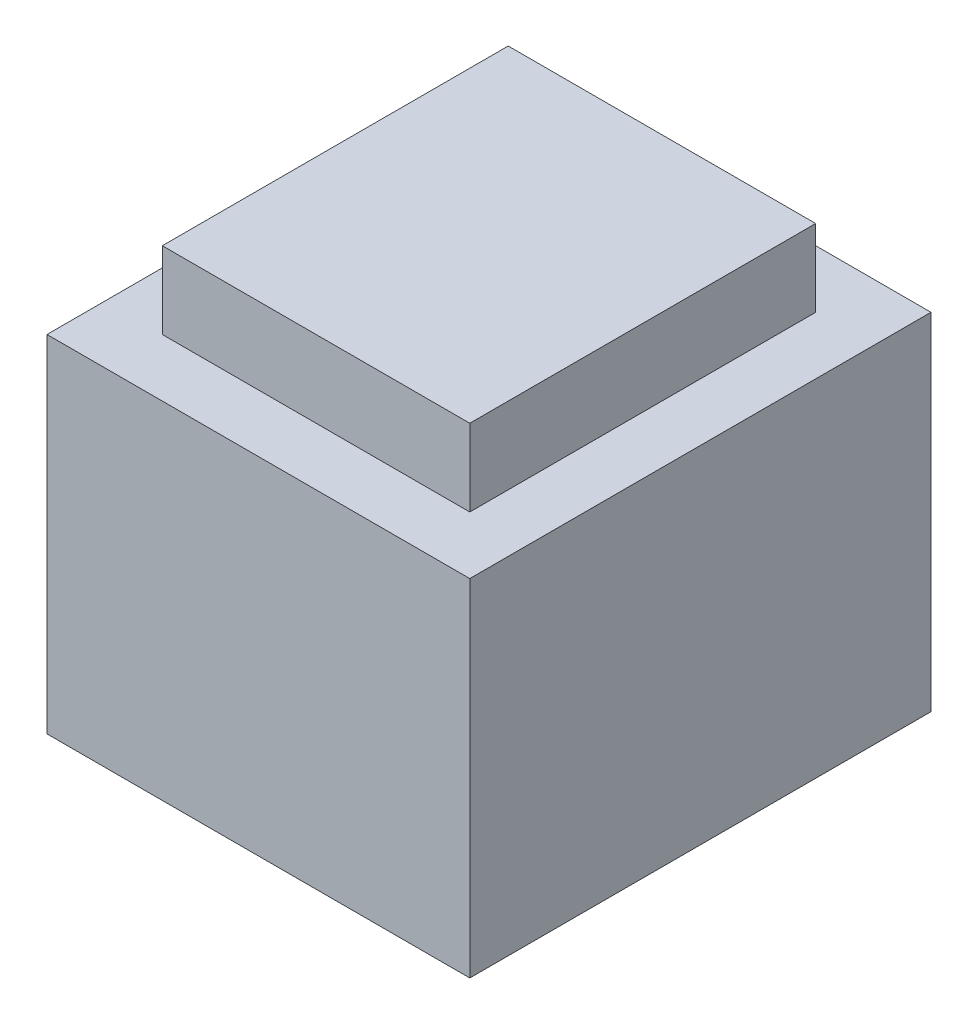
SolidWorks part; units mm, degrees
ref_plane "Front Plane" through (0, 0, 0) normal (0, 0, 1) x (1, 0, 0)
ref_plane "Top Plane" through (0, 0, 0) normal (0, 1, 0) x (1, 0, 0)
ref_plane "Right Plane" through (0, 0, 0) normal (1, 0, 0) x (0, 0, -1)
sketch "Эскиз1" plane through (0, 0, 0) normal (0, 1, 0) x (1, 0, 0)
  line L1 (5.5, -6) -> (-5.5, -6)
  line L2 (5.5, -6) -> (5.5, 6)
  line L3 (5.5, 6) -> (-5.5, 6)
  line L4 (-5.5, -6) -> (-5.5, 6)
  line L5 (5.5, -6) -> (-5.5, 6) construction
  line L6 (5.5, 6) -> (-5.5, -6) construction
  point P0 (0, 0)
  dimension "D1" = 12
  dimension "D2" = 11
extrude "Бобышка-Вытянуть1" add sketch "Эскиз1" along normal blind 9
sketch "Эскиз2" plane through (0, 9, 0) normal (0, 1, 0) x (1, 0, 0)
  line L1 (-4, 4.5) -> (4, 4.5)
  line L2 (-4, 4.5) -> (-4, -4.5)
  line L3 (-4, -4.5) -> (4, -4.5)
  line L4 (4, 4.5) -> (4, -4.5)
  line L5 (-4, 4.5) -> (4, -4.5) construction
  line L6 (-4, -4.5) -> (4, 4.5) construction
  point P0 (0, 0)
  dimension "D1" = 9
  dimension "D2" = 8
extrude "Бобышка-Вытянуть2" add sketch "Эскиз2" along normal blind 2
